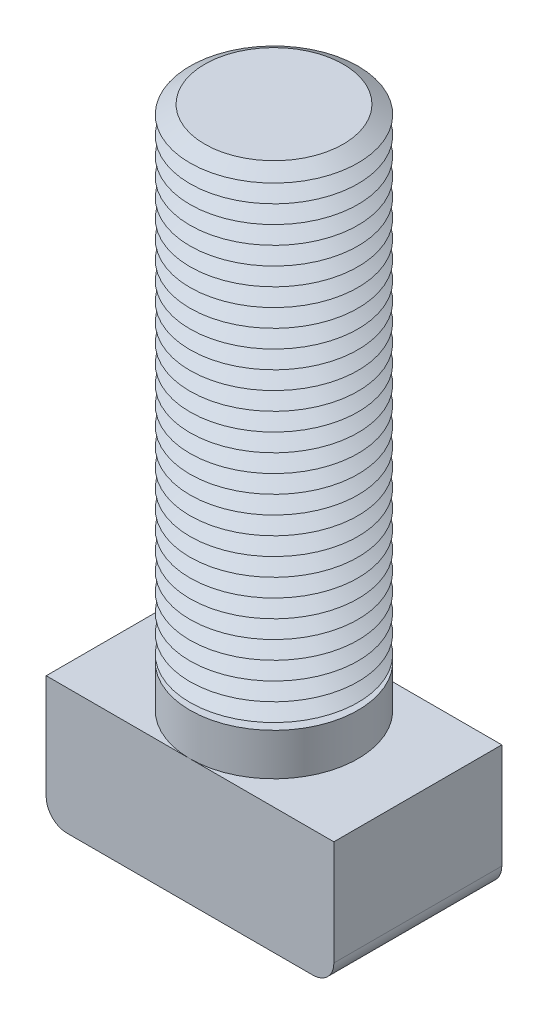
SolidWorks part; units mm, degrees
ref_plane "前视基准面" through (0, 0, 0) normal (0, 0, 1) x (1, 0, 0)
ref_plane "上视基准面" through (0, 0, 0) normal (0, 1, 0) x (1, 0, 0)
ref_plane "右视基准面" through (0, 0, 0) normal (1, 0, 0) x (0, 0, -1)
sketch "草图1" plane through (0, 0, 0) normal (0, 0, 1) x (1, 0, 0)
  line B0 (5.85, -6) -> (-5.85, -6)
  line B1 (6.85, -5) -> (6.85, 0)
  line B2 (6.85, 0) -> (-6.85, 0)
  line B3 (-6.85, -5) -> (-6.85, 0)
  arc B4 (5.85, -6) -> (6.85, -5) centre (5.85, -5) ccw
  arc B5 (-6.85, -5) -> (-5.85, -6) centre (-5.85, -5) ccw
sketch_block_instance "A$C7F5E00EB-1"
sketch_block "A$C7F5E00EB"
extrude "凸台-拉伸1" add sketch "草图1" along normal mid plane 8
sketch "草图3" plane through (0, 0, 0) normal (0, 0, 1) x (1, 0, 0)
  line B0 (0, 25) -> (0, 0)
  line B1 (4, 0) -> (0, 0)
  line B2 (4, 0) -> (4, 2)
  line B3 (3.3, 25) -> (0, 25)
  line B4 (3.3, 25) -> (4, 24.5721)
  line B5 (3.3, 24.1442) -> (4, 24.5721)
  line B6 (3.3, 24.1442) -> (4, 23.7163)
  line B7 (3.3, 23.2884) -> (4, 23.7163)
  line B8 (3.3, 23.2884) -> (4, 22.8605)
  line B9 (3.3, 22.4326) -> (4, 22.8605)
  line B10 (3.3, 22.4326) -> (4, 22.0046)
  line B11 (3.3, 21.5767) -> (4, 22.0046)
  line B12 (3.3, 21.5767) -> (4, 21.1488)
  line B13 (3.3, 20.7209) -> (4, 21.1488)
  line B14 (3.3, 20.7209) -> (4, 20.293)
  line B15 (3.3, 19.8651) -> (4, 20.293)
  line B16 (3.3, 19.8651) -> (4, 19.4372)
  line B17 (3.3, 19.0093) -> (4, 19.4372)
  line B18 (3.3, 19.0093) -> (4, 18.5814)
  line B19 (3.3, 18.1535) -> (4, 18.5814)
  line B20 (3.3, 18.1535) -> (4, 17.7256)
  line B21 (3.3, 17.2977) -> (4, 17.7256)
  line B22 (3.3, 17.2977) -> (4, 16.8697)
  line B23 (3.3, 16.4418) -> (4, 16.8697)
  line B24 (3.3, 16.4418) -> (4, 16.0139)
  line B25 (3.3, 15.586) -> (4, 16.0139)
  line B26 (3.3, 15.586) -> (4, 15.1581)
  line B27 (3.3, 14.7302) -> (4, 15.1581)
  line B28 (3.3, 14.7302) -> (4, 14.3023)
  line B29 (3.3, 13.8744) -> (4, 14.3023)
  line B30 (3.3, 13.8744) -> (4, 13.4465)
  line B31 (3.3, 13.0186) -> (4, 13.4465)
  line B32 (3.3, 13.0186) -> (4, 12.5907)
  line B33 (3.3, 12.1628) -> (4, 12.5907)
  line B34 (3.3, 12.1628) -> (4, 11.7348)
  line B35 (3.3, 11.3069) -> (4, 11.7348)
  line B36 (3.3, 11.3069) -> (4, 10.879)
  line B37 (3.3, 10.4511) -> (4, 10.879)
  line B38 (3.3, 10.4511) -> (4, 10.0232)
  line B39 (3.3, 9.5953) -> (4, 10.0232)
  line B40 (3.3, 9.5953) -> (4, 9.1674)
  line B41 (3.3, 8.7395) -> (4, 9.1674)
  line B42 (3.3, 8.7395) -> (4, 8.3116)
  line B43 (3.3, 7.8837) -> (4, 8.3116)
  line B44 (3.3, 7.8837) -> (4, 7.4558)
  line B45 (3.3, 7.0279) -> (4, 7.4558)
  line B46 (3.3, 7.0279) -> (4, 6.5999)
  line B47 (3.3, 6.172) -> (4, 6.5999)
  line B48 (3.3, 6.172) -> (4, 5.7441)
  line B49 (3.3, 5.3162) -> (4, 5.7441)
  line B50 (3.3, 5.3162) -> (4, 4.8883)
  line B51 (3.3, 4.4604) -> (4, 4.8883)
  line B52 (3.3, 4.4604) -> (4, 4.0325)
  line B53 (3.3, 3.6046) -> (4, 4.0325)
  line B54 (3.3, 3.6046) -> (4, 3.1767)
  line B55 (3.3, 2.7488) -> (4, 3.1767)
  line B56 (3.3, 2.7488) -> (4, 2.3209)
  line B57 (3.4751, 2) -> (4, 2.3209)
  line B58 (4, 2) -> (3.4751, 2)
sketch_block_instance "A$C0EFC591C-1"
sketch_block "A$C0EFC591C"
revolve "旋转1" add sketch "草图3" angle 360 about L0
